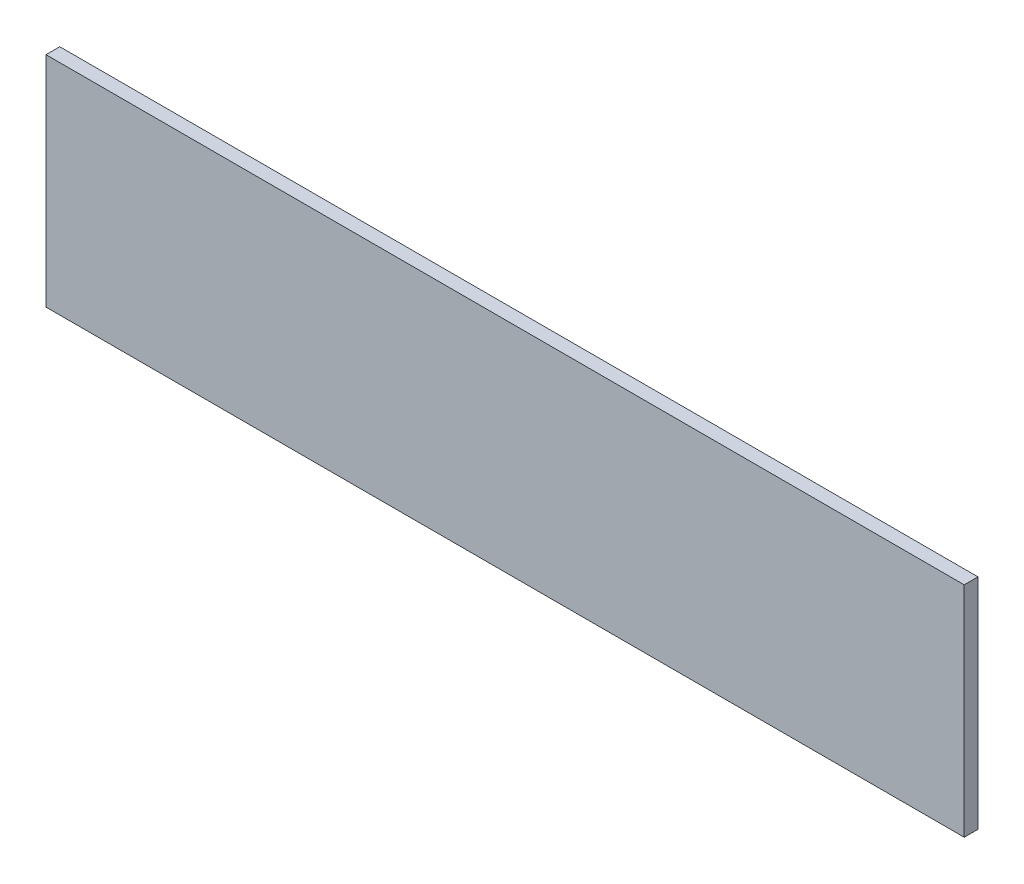
SolidWorks part; units mm, degrees
ref_plane "Front Plane" through (0, 0, 0) normal (0, 0, 1) x (1, 0, 0)
ref_plane "Top Plane" through (0, 0, 0) normal (0, 1, 0) x (1, 0, 0)
ref_plane "Right Plane" through (0, 0, 0) normal (1, 0, 0) x (0, 0, -1)
sketch "Sketch1" plane through (0, 0, 0) normal (0, 0, 1) x (1, 0, 0)
  line L1 (-53.34, -12.7) -> (53.34, -12.7)
  line L2 (-53.34, -12.7) -> (-53.34, 12.7)
  line L3 (-53.34, 12.7) -> (53.34, 12.7)
  line L4 (53.34, -12.7) -> (53.34, 12.7)
  line L5 (-53.34, -12.7) -> (53.34, 12.7) construction
  line L6 (-53.34, 12.7) -> (53.34, -12.7) construction
  point P0 (0, 0)
  dimension "D1" = 106.68
  dimension "D2" = 25.4
extrude "Boss-Extrude1" add sketch "Sketch1" along normal blind 1.6
